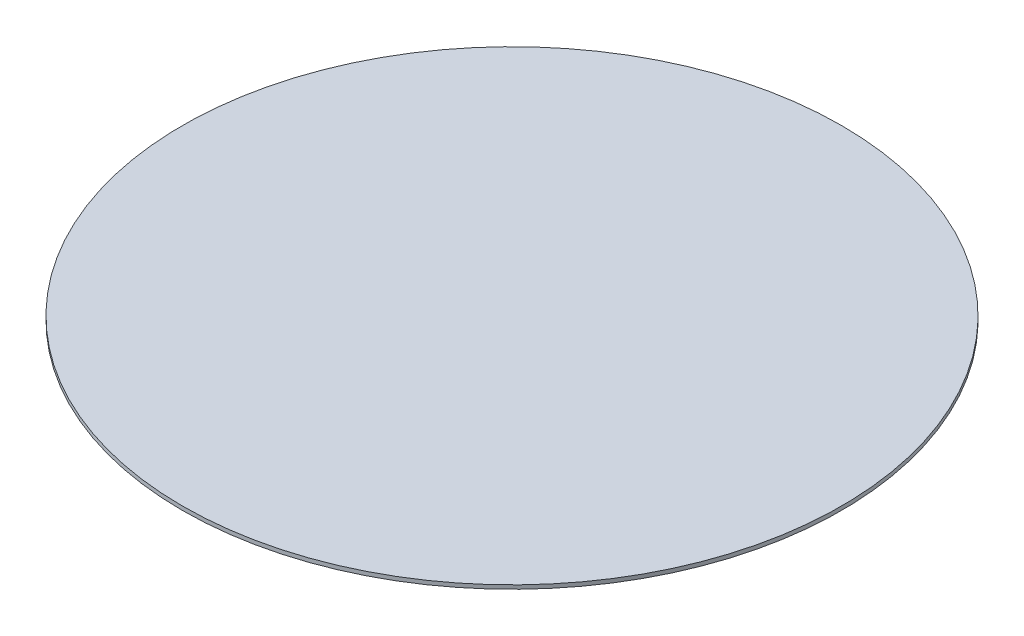
SolidWorks part; units mm, degrees
ref_plane "Front Plane" through (0, 0, 0) normal (0, 0, 1) x (1, 0, 0)
ref_plane "Top Plane" through (0, 0, 0) normal (0, 1, 0) x (1, 0, 0)
ref_plane "Right Plane" through (0, 0, 0) normal (1, 0, 0) x (0, 0, -1)
sketch "Sketch1" plane through (0, 0, 0) normal (0, 1, 0) x (1, 0, 0)
  circle A0 centre (0, 0) radius 10.8437
  dimension "D1" = 21.6875
extrude "Boss-Extrude1" add sketch "Sketch1" along normal blind 0.127
equation "\"magnet_inset\"= 0.0625in"
equation "\"magnet_diameter\"= 0.2in"
equation "\"steel_inset_distance\"= 1in / 32"
equation "\"kapton_thickness\"= 0.005in"
equation "\"pcb_thickness\"= 0.6mm"
equation "\"magnet_thickness\"= 0.03125in"
equation "\"edge_radius\"= 1in / 10"
equation "\"card_width\"= 78mm"
equation "\"card_height\"= 50mm"
equation "\"battery_diameter\"= 20mm"
equation "\"battery_oversize\"= 0.1mm"
equation "\"battery_vertical_inset\"= 1in / 16"
equation "\"battery_horizontal_inset\"= 1in / 4"
equation "\"battery_spacing\"= 1in / 16"
equation "\"battery_thickness\"= 1.6mm"
equation "\"battery_cap_oversize\"= 1in / 16"
equation "\"D1@Sketch1\"=\"battery_diameter\"+\"battery_oversize\"+\"battery_cap_oversize\""
equation "\"battery_cap_thickness\"= 0.005in"
equation "\"D1@Boss-Extrude1\"=\"battery_cap_thickness\""
